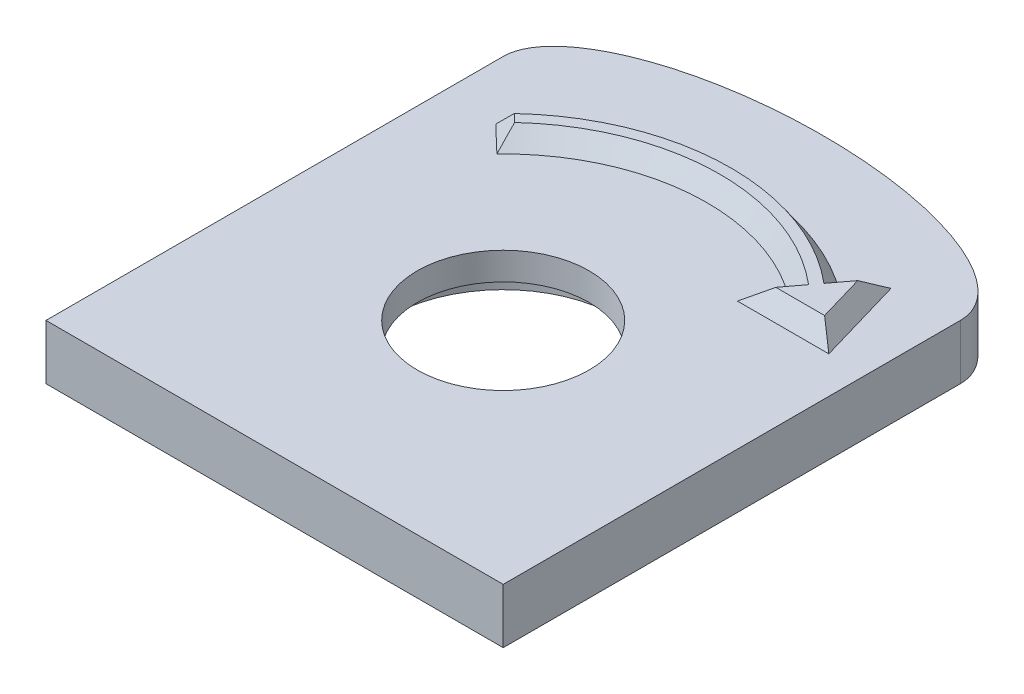
SolidWorks part; units mm, degrees
ref_plane "Front Plane" through (0, 0, 0) normal (0, 0, 1) x (1, 0, 0)
ref_plane "Top Plane" through (0, 0, 0) normal (0, 1, 0) x (1, 0, 0)
ref_plane "Right Plane" through (0, 0, 0) normal (1, 0, 0) x (0, 0, -1)
sketch "Sketch1" plane through (0, 0, 0) normal (0, 1, 0) x (1, 0, 0)
  line L2 (-12.732, 9.8969) -> (-12.732, -15.1031)
  line L3 (-12.732, -15.1031) -> (12.268, -15.1031)
  line L4 (12.268, 9.8969) -> (12.268, -15.1031)
  circle A0 centre (-0.232, -2.6031) radius 4.7
  ellipse E0 centre (-0.232, 9.8969) end of major axis (-12.732, 9.8969) minor radius 5 (12.268, 9.8969) -> (-12.732, 9.8969) ccw
  dimension "D3" = 9.4
  dimension "D1" = 25
  dimension "D2" = 25
  dimension "D4" = 5
extrude "Boss-Extrude1" add sketch "Sketch1" along normal blind 3
sketch "Sketch3" plane through (0, 3, 0) normal (0, 1, 0) x (1, 0, 0)
  line L1 (-9.7303, 6.4877) -> (-8.2854, 5.1048)
  line L3 (6.4566, 6.3151) -> (5.2566, 4.7151)
  line L4 (5.2566, 4.7151) -> (6.4566, 6.3151)
  line L5 (7.6566, 7.9151) -> (8.8566, 9.5151)
  line L6 (8.8566, 9.5151) -> (10.2566, 4.7151)
  line L7 (10.2566, 4.7151) -> (5.2566, 4.7151)
  arc A0 (7.6566, 7.9151) -> (-9.7303, 6.4877) centre (-0.232, -2.6031) ccw
  arc A1 (6.4566, 6.3151) -> (-8.2854, 5.1048) centre (-0.232, -2.6031) ccw
  dimension "D1" = 2
  dimension "D2" = 2
  dimension "D3" = 2
  dimension "D4" = 5
  dimension "D5" = 5
extrude "Boss-Extrude2" add sketch "Sketch3" along normal blind 1 draft 35 contours A1 L3 L7 L6 L5 A0 L1
sketch "Sketch6" plane through (0, 0, 0) normal (0, -1, 0) x (1, 0, 0)
  circle A0 centre (-0.232, 2.6031) radius 6.3
  dimension "D1" = 12.6
extrude "Cut-Extrude1" cut sketch "Sketch6" against normal blind 1.5
